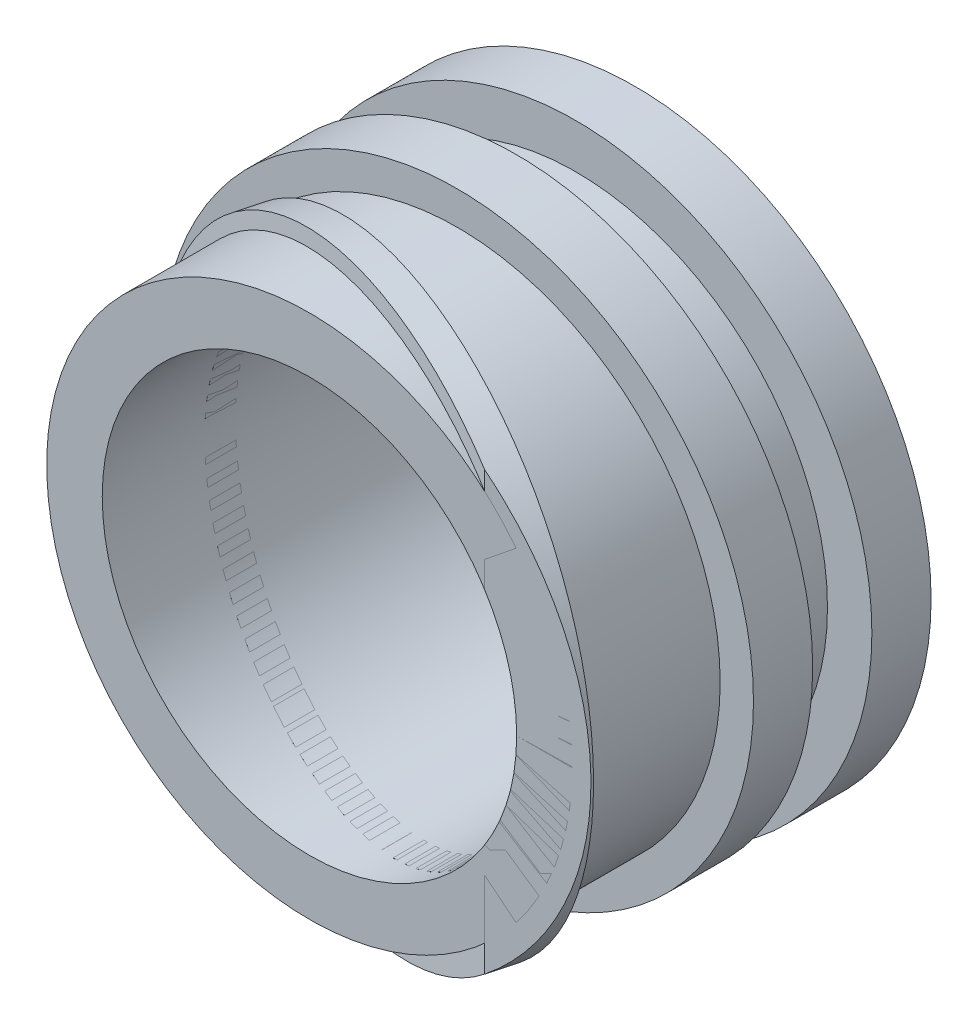
SolidWorks part; units mm, degrees
material "ABS"
ref_plane "Front Plane" through (0, 0, 0) normal (0, 0, 1) x (1, 0, 0)
ref_plane "Top Plane" through (0, 0, 0) normal (0, 1, 0) x (1, 0, 0)
ref_plane "Right Plane" through (0, 0, 0) normal (1, 0, 0) x (0, 0, -1)
sketch "Sketch1" plane through (0, 0, 0) normal (0, 0, 1) x (1, 0, 0)
  circle A0 centre (0, 0) radius 10
extrude "Boss-Extrude1" add sketch "Sketch1" along normal blind 2
sketch "Sketch2" plane through (0, 0, 0) normal (0, 0, 1) x (1, 0, 0)
  circle A0 centre (0, 0) radius 8.5
  dimension "D1" = 17
extrude "Boss-Extrude2" add sketch "Sketch2" along normal blind 6
sketch "Sketch3" plane through (0, 0, 0) normal (0, 0, 1) x (1, 0, 0)
  circle A0 centre (0, 0) radius 10
extrude "Boss-Extrude3" add sketch "Sketch3" along normal blind 2 from offset 4
sketch "Sketch5" plane through (0, 0, 0) normal (0, 0, 1) x (1, 0, 0)
  circle A0 centre (0, 0) radius 7
extrude "Cut-Extrude2" cut sketch "Sketch5" along normal through all
sketch "Sketch6" plane through (0, 0, 0) normal (0, 0, 1) x (1, 0, 0)
  circle A0 centre (0, 0) radius 7
  circle A1 centre (0, 0) radius 8.875
  dimension "D1" = 17.75
extrude "Boss-Extrude4" add sketch "Sketch6" along normal blind 5 from surface at 6 starting at face at (10, 0, 6)
ref_plane "Plane1" through (0, 0, 6) normal (0, 0, 1) x (1, 0, 0)
sketch "Sketch7" plane through (0, 0, 6) normal (0, 0, 1) x (1, 0, 0)
  line L0 (-8.875, -10.0832) -> (-8.875, 9.9371)
ref_plane "Plane2" through (-2.0945, 0, 7.8168) normal (-0.2588, 0, 0.9659) x (0.9659, 0, 0.2588)
sketch "Sketch8" plane through (-2.0945, 0, 7.8168) normal (-0.2588, 0, 0.9659) x (0.9659, 0, 0.2588)
  circle A0 centre (2.4505, -0.134) radius 9.5831
extrude "Boss-Extrude5" add sketch "Sketch8" along normal blind 1 separate body
sketch "Sketch10" plane through (0, 0, 0) normal (0, 0, 1) x (1, 0, 0)
  circle A0 centre (0, 0) radius 7
extrude "Cut-Extrude4" cut sketch "Sketch10" along normal through all
sketch "Sketch12" plane through (0, 0, 0) normal (1, 0, 0) x (0, 0, -1)
  line L0 (-11, 8.875) -> (-11, -8.875)
  line L1 (-11, 8.875) -> (-11, -8.875) construction
  line L3 (-11, 8.875) -> (-11.9151, 8.875)
  line L5 (-11, -8.875) -> (-11.9151, -8.875)
  line L6 (-11.9151, 8.875) -> (-11.9151, -8.875)
extrude "Cut-Extrude5" cut sketch "Sketch12" along normal blind 10
